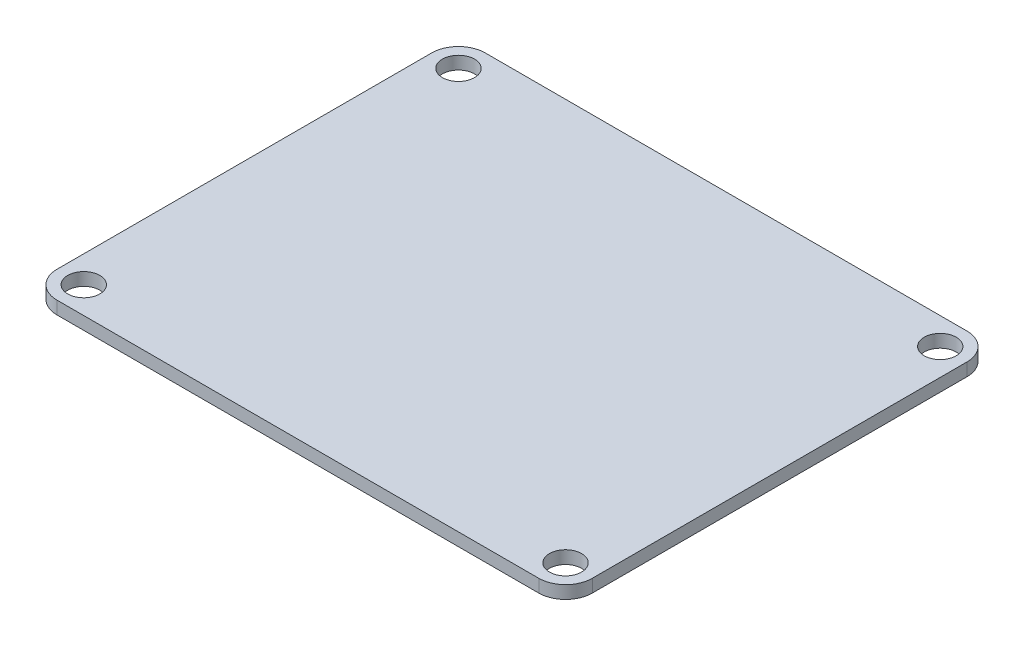
SolidWorks part; units mm, degrees
material "有机玻璃 (TM) GS 丙烯酸铸钣"
ref_plane "前视基准面" through (0, 0, 0) normal (0, 0, 1) x (1, 0, 0)
ref_plane "上视基准面" through (0, 0, 0) normal (0, 1, 0) x (1, 0, 0)
ref_plane "右视基准面" through (0, 0, 0) normal (1, 0, 0) x (0, 0, -1)
sketch "草图1" plane through (0, 0, 0) normal (0, 1, 0) x (1, 0, 0)
  line L1 (-55.214, 19.5444) -> (-10.214, 19.5444)
  line L2 (-57.714, 17.0444) -> (-57.714, -17.9556)
  line L3 (-55.214, -20.4556) -> (-10.214, -20.4556)
  line L4 (-7.714, 17.0444) -> (-7.714, -17.9556)
  arc A0 (-55.214, 19.5444) -> (-57.714, 17.0444) centre (-55.214, 17.0444) ccw
  arc A1 (-7.714, 17.0444) -> (-10.214, 19.5444) centre (-10.214, 17.0444) ccw
  arc A2 (-57.714, -17.9556) -> (-55.214, -20.4556) centre (-55.214, -17.9556) ccw
  arc A3 (-10.214, -20.4556) -> (-7.714, -17.9556) centre (-10.214, -17.9556) ccw
extrude "凸台-拉伸3" add sketch "草图1" along normal blind 1.2
sketch "草图7" plane through (0, 1.2, 0) normal (0, 1, 0) x (1, 0, 0)
  circle A4 centre (-55.214, 17.0444) radius 1.5
  circle A5 centre (-10.214, 17.0444) radius 1.5
  circle A6 centre (-55.214, -17.9556) radius 1.5
  circle A7 centre (-10.214, -17.9556) radius 1.5
extrude "切除-拉伸1" cut sketch "草图7" against normal through all
